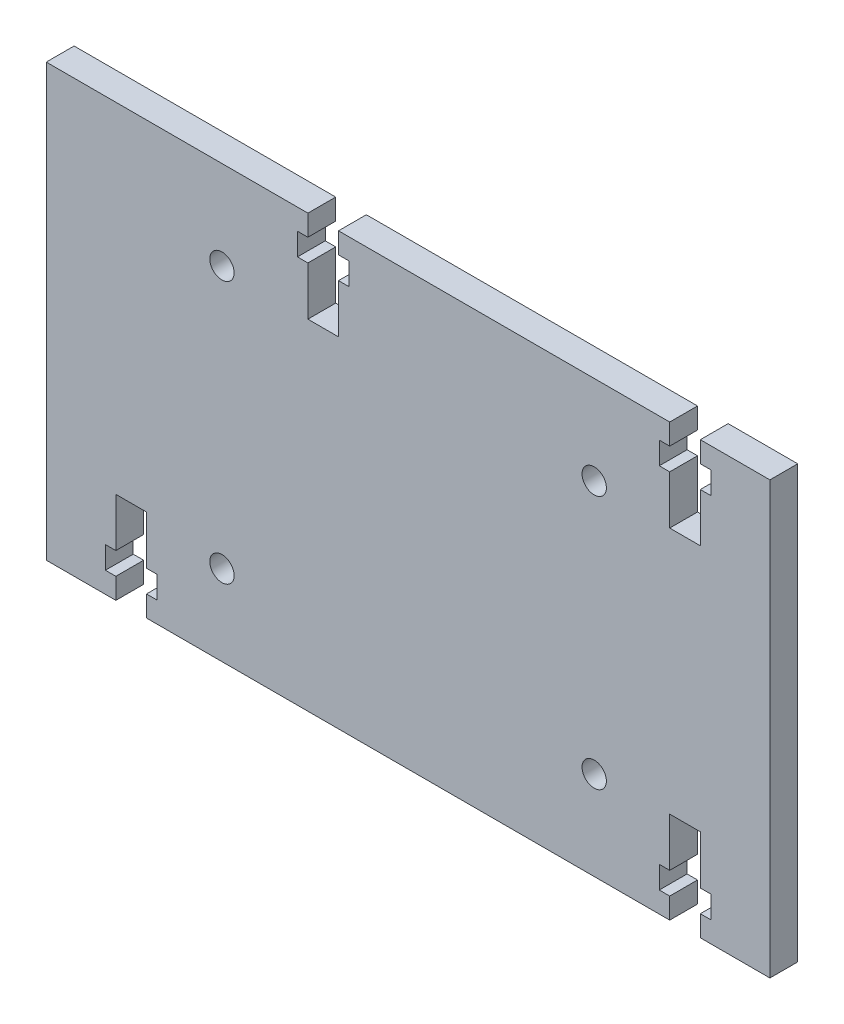
SolidWorks part; units mm, degrees
ref_plane "Front Plane" through (0, 0, 0) normal (0, 0, 1) x (1, 0, 0)
ref_plane "Top Plane" through (0, 0, 0) normal (0, 1, 0) x (1, 0, 0)
ref_plane "Right Plane" through (0, 0, 0) normal (1, 0, 0) x (0, 0, -1)
sketch "Sketch1" plane through (0, 0, 0) normal (0, 0, 1) x (1, 0, 0)
  line L1 (-52, 31) -> (52, 31)
  line L2 (-52, 31) -> (-52, -31)
  line L3 (-52, -31) -> (52, -31)
  line L4 (52, 31) -> (52, -31)
  dimension "D1" = 104
  dimension "D2" = 62
  dimension "D3" = 31
  dimension "D4" = 52
extrude "Boss-Extrude1" add sketch "Sketch1" along normal blind 4
sketch "Sketch2" plane through (0, 0, 0) normal (0, 0, -1) x (-1, 0, 0)
  line L0 (-39.8, -31) -> (-39.8, -16.1548) construction
  line L1 (-37.6, -28) -> (-37.6, -31)
  line L2 (-42, -24.8) -> (-42, -17.8)
  line L3 (-36.1, -24.8) -> (-37.6, -24.8)
  line L4 (-36.1, -28) -> (-36.1, -24.8)
  line L5 (-37.6, -28) -> (-36.1, -28)
  line L6 (-43.5, -24.8) -> (-42, -24.8)
  line L7 (-43.5, -28) -> (-43.5, -24.8)
  line L8 (-42, -28) -> (-43.5, -28)
  line L9 (-42, -31) -> (-37.6, -31)
  line L10 (-37.6, -17.8) -> (-37.6, -24.8)
  line L11 (-42, -17.8) -> (-37.6, -17.8)
  line L12 (-42, -31) -> (-42, -28)
  line L13 (52, -31) -> (-52, -31) construction
  line L14 (-52, -31) -> (-52, 31) construction
  line L15 (0, 0) -> (0, -16.1548) construction
  line L16 (0, 0) -> (21.3086, 0) construction
  line L17 (39.8, -31) -> (39.8, -16.1548) construction
  line L18 (42, -31) -> (42, -28)
  line L19 (42, -17.8) -> (37.6, -17.8)
  line L20 (37.6, -17.8) -> (37.6, -24.8)
  line L21 (42, -31) -> (37.6, -31)
  line L22 (42, -28) -> (43.5, -28)
  line L23 (43.5, -28) -> (43.5, -24.8)
  line L24 (43.5, -24.8) -> (42, -24.8)
  line L25 (37.6, -28) -> (36.1, -28)
  line L26 (36.1, -28) -> (36.1, -24.8)
  line L27 (36.1, -24.8) -> (37.6, -24.8)
  line L28 (42, -24.8) -> (42, -17.8)
  line L29 (37.6, -28) -> (37.6, -31)
  line L30 (12.2, 21.6) -> (12.2, 36.4452) construction
  line L43 (-39.8, 31) -> (-39.8, 16.1548) construction
  line L44 (-42, 31) -> (-42, 28)
  line L45 (-42, 17.8) -> (-37.6, 17.8)
  line L46 (-37.6, 17.8) -> (-37.6, 24.8)
  line L47 (-42, 31) -> (-37.6, 31)
  line L48 (-42, 28) -> (-43.5, 28)
  line L49 (-43.5, 28) -> (-43.5, 24.8)
  line L50 (-43.5, 24.8) -> (-42, 24.8)
  line L51 (-37.6, 28) -> (-36.1, 28)
  line L52 (-36.1, 28) -> (-36.1, 24.8)
  line L53 (-36.1, 24.8) -> (-37.6, 24.8)
  line L54 (-42, 24.8) -> (-42, 17.8)
  line L55 (-37.6, 28) -> (-37.6, 31)
  line L56 (14.4, 24.8) -> (14.4, 17.8)
  line L57 (10, 28) -> (10, 31)
  line L58 (15.9, 28) -> (14.4, 28)
  line L59 (15.9, 24.8) -> (15.9, 28)
  line L60 (14.4, 24.8) -> (15.9, 24.8)
  line L61 (8.5, 28) -> (10, 28)
  line L62 (8.5, 24.8) -> (8.5, 28)
  line L63 (10, 24.8) -> (8.5, 24.8)
  line L64 (10, 17.8) -> (14.4, 17.8)
  line L65 (14.4, 31) -> (14.4, 28)
  line L66 (10, 31) -> (14.4, 31)
  line L67 (10, 17.8) -> (10, 24.8)
  line L68 (-52, 31) -> (52, 31) construction
  dimension "D1" = 7
  dimension "D2" = 3.2
  dimension "D3" = 3
  dimension "D4" = 2.2
  dimension "D5" = 4.4
  dimension "D6" = 1.5
  dimension "D7" = 1.5
  dimension "D8" = 10
  dimension "D9" = 3
  dimension "D10" = 3.2
  dimension "D11" = 7
  dimension "D12" = 2.2
  dimension "D13" = 4.4
  dimension "D14" = 1.5
  dimension "D15" = 1.5
  dimension "D16" = 10
extrude "Cut-Extrude1" cut sketch "Sketch2" against normal blind 10
sketch "Sketch3" plane through (0, 0, 0) normal (0, 0, -1) x (-1, 0, 0)
  line L0 (25, -7.2022) -> (35, -7.2022) construction
  line L3 (25, -4.7022) -> (35, -4.7022)
  line L4 (25, -9.7022) -> (35, -9.7022)
  line L5 (-25, -7.4103) -> (-35, -7.4103) construction
  line L8 (-25, -9.9103) -> (-35, -9.9103)
  line L9 (-25, -4.9103) -> (-35, -4.9103)
  line L10 (-52, -31) -> (-52, 31) construction
  line L11 (52, 31) -> (52, -31) construction
  arc A0 (25, -4.7022) -> (25, -9.7022) centre (25, -7.2022) ccw
  arc A1 (35, -9.7022) -> (35, -4.7022) centre (35, -7.2022) ccw
  arc A2 (-25, -9.9103) -> (-25, -4.9103) centre (-25, -7.4103) ccw
  arc A3 (-35, -4.9103) -> (-35, -9.9103) centre (-35, -7.4103) ccw
  point P6 (30, -7.2022)
  point P11 (-30, -7.4103)
  dimension "D1" = 10
  dimension "D2" = 10
  dimension "D3" = 17
  dimension "D4" = 17
  dimension "D5" = 5
  dimension "D6" = 5
extrude "Cut-Extrude2" [suppressed] cut sketch "Sketch3" against normal blind 10
sketch "Sketch4" plane through (0, 0, 0) normal (0, 0, -1) x (-1, 0, 0)
  line L0 (0, 0) -> (0, 44.8161) construction
  line L1 (0, 0) -> (-66.7466, 0) construction
  circle A0 centre (-26.75, 18.25) radius 1.75
  circle A1 centre (-26.75, -18.25) radius 1.75
  circle A2 centre (26.75, 18.25) radius 1.75
  circle A3 centre (26.75, -19.4158) radius 1.75
  dimension "D2" = 3.5
  dimension "D3" = 3.5
  dimension "D4" = 3.5
  dimension "D5" = 3.5
  dimension "D1" = 36.5
  dimension "D6" = 53.5
  dimension "D7" = 18.25
  dimension "D8" = 26.75
extrude "Cut-Extrude3" cut sketch "Sketch4" against normal blind 10
